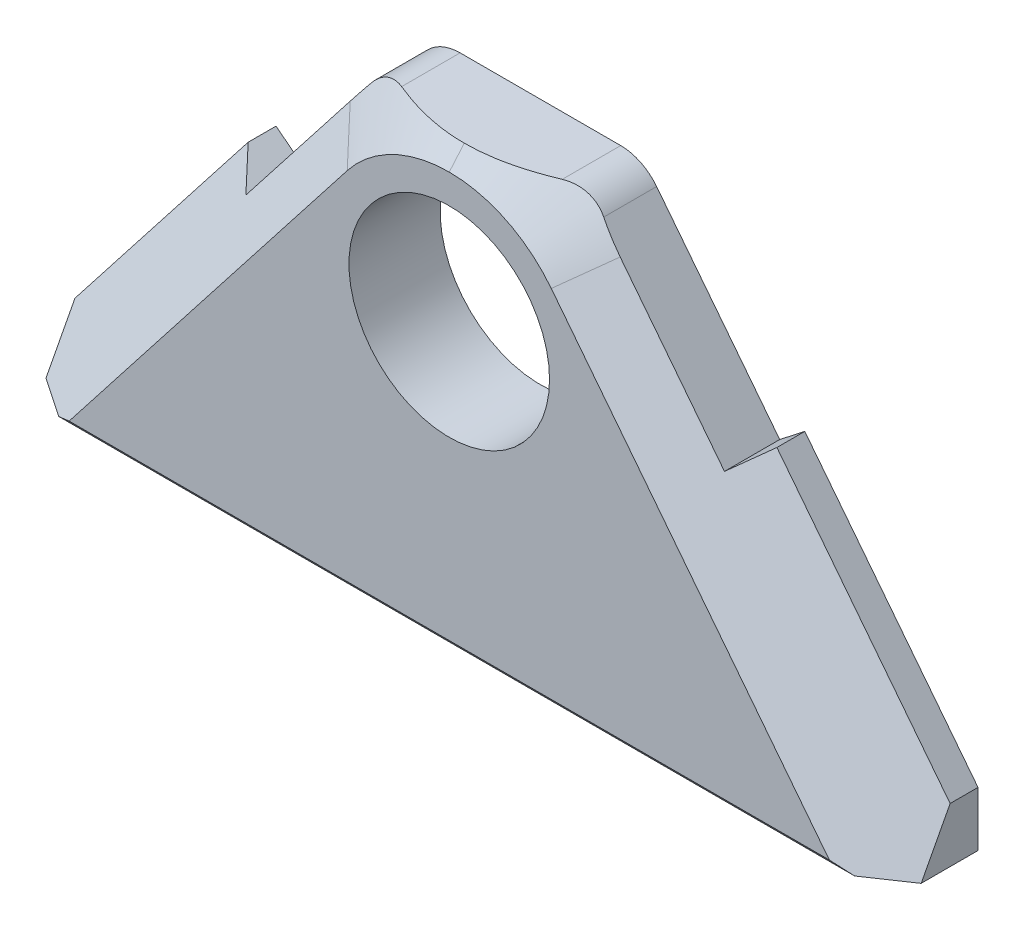
SolidWorks part; units mm, degrees
other "Markup1"
sketch "Sketch4" plane through (96, 0, 20) normal (0.9947, 0.0311, 0.0982) x (0.0936, 0.1251, -0.9877)
other "Markup3"
sketch "Sketch6" plane through (96, 0, 20) normal (0.9947, 0.0311, 0.0982) x (0.0936, 0.1251, -0.9877)
other "Markup4"
sketch "Sketch7" plane through (96, 0, 20) normal (0.9947, 0.0311, 0.0982) x (0.0936, 0.1251, -0.9877)
ref_plane "Front Plane" through (0, 0, 0) normal (0, 0, 1) x (1, 0, 0)
ref_plane "Top Plane" through (0, 0, 0) normal (0, 1, 0) x (1, 0, 0)
ref_plane "Right Plane" through (0, 0, 0) normal (1, 0, 0) x (0, 0, -1)
sketch "Sketch1" plane through (0, 0, 0) normal (0, 0, 1) x (1, 0, 0)
  line L0 (-17.6163, 0) -> (17.6163, 0)
  line L1 (25.4964, -3.8434) -> (52.5, -38.4064)
  line L2 (52.5, -38.4064) -> (58, -34.1094)
  line L3 (58, -34.1094) -> (96, -82.7471)
  line L4 (96, -82.7471) -> (96, -94.7471)
  line L5 (96, -94.7471) -> (-96, -94.7471)
  line L6 (0, -94.7471) -> (0, 0) construction
  line L7 (-96, -82.7471) -> (-96, -94.7471)
  line L8 (-58, -34.1094) -> (-96, -82.7471)
  line L9 (-52.5, -38.4064) -> (-58, -34.1094)
  line L10 (-25.4964, -3.8434) -> (-52.5, -38.4064)
  circle A0 centre (0, -32.2471) radius 22
  arc A1 (-25.4964, -3.8434) -> (-17.6163, 0) centre (-17.6163, -10) cw
  arc A2 (17.6163, 0) -> (25.4964, -3.8434) centre (17.6163, -10) cw
  point P19 (-22.4936, 0)
  point P22 (22.4936, 0)
  point P23 (22, -1.0121)
  point P24 (-22, -1.0121)
  dimension "D1" = 10
  dimension "D8" = 44
  dimension "D2" = 44
  dimension "D3" = 192
  dimension "D4" = 12
  dimension "D5" = 38
  dimension "D6" = 105
  dimension "D7" = 116
  dimension "D9" = 62.5
extrude "Boss-Extrude1" add sketch "Sketch1" along normal blind 20
sketch "Sketch2" plane through (0, 0, 20) normal (0, 0, 1) x (1, 0, 0)
  line L0 (96, -82.7471) -> (58, -34.1094) construction
  line L1 (96, -94.7471) -> (96, -82.7471) construction
  line L2 (-96, -94.7471) -> (96, -94.7471) construction
  line L3 (-96, -82.7471) -> (-96, -94.7471) construction
  line L4 (-58, -34.1094) -> (-96, -82.7471) construction
  line L5 (96, -82.7471) -> (58, -34.1094)
  line L6 (96, -94.7471) -> (96, -82.7471)
  line L7 (-96, -94.7471) -> (96, -94.7471)
  line L8 (-96, -82.7471) -> (-96, -94.7471)
  line L9 (-58, -34.1094) -> (-96, -82.7471)
  line L10 (23.8823, -13.5882) -> (87.2907, -94.7471)
  line L11 (0, 0) -> (0, -96.6519) construction
  line L12 (-23.8823, -13.5882) -> (-87.2907, -94.7471)
  line L13 (52.5, -38.4064) -> (25.4964, -3.8434) construction
  line L14 (52.5, -38.4064) -> (25.4964, -3.8434)
  line L15 (-87.2907, -94.7471) -> (87.2907, -94.7471)
  line L26 (58, -34.1094) -> (52.5, -38.4064)
  line L27 (96, -82.7471) -> (58, -34.1094)
  line L28 (96, -94.7471) -> (96, -82.7471)
  line L29 (-96, -94.7471) -> (96, -94.7471)
  line L30 (-96, -82.7471) -> (-96, -94.7471)
  line L31 (-58, -34.1094) -> (-96, -82.7471)
  line L32 (-52.5, -38.4064) -> (-58, -34.1094)
  line L33 (-25.4964, -3.8434) -> (-52.5, -38.4064)
  line L34 (17.6163, 0) -> (-17.6163, 0)
  line L35 (52.5, -38.4064) -> (25.4964, -3.8434)
  line L36 (58, -34.1094) -> (52.5, -38.4064)
  line L37 (96, -82.7471) -> (58, -34.1094)
  line L38 (96, -94.7471) -> (96, -82.7471)
  line L39 (-96, -94.7471) -> (96, -94.7471)
  line L40 (-96, -82.7471) -> (-96, -94.7471)
  line L41 (-58, -34.1094) -> (-96, -82.7471)
  line L42 (-52.5, -38.4064) -> (-58, -34.1094)
  line L43 (-25.4964, -3.8434) -> (-52.5, -38.4064)
  line L44 (17.6163, 0) -> (-17.6163, 0)
  line L45 (52.5, -38.4064) -> (25.4964, -3.8434)
  arc A0 (-23.8823, -13.5882) -> (23.8823, -13.5882) centre (0, -32.2471) cw
  arc A3 (-17.6163, 0) -> (-25.4964, -3.8434) centre (-17.6163, -10) ccw
  arc A4 (25.4964, -3.8434) -> (17.6163, 0) centre (17.6163, -10) ccw
  arc A5 (-17.6163, 0) -> (-25.4964, -3.8434) centre (-17.6163, -10) ccw
  arc A6 (25.4964, -3.8434) -> (17.6163, 0) centre (17.6163, -10) ccw
  point P9 (0, -1.94)
  dimension "D1" = 52
  dimension "D2" = 0
  dimension "D3" = 1.94
sketch "Sketch3" plane through (0, 0, 0) normal (1, 0, 0) x (0, 0, -1)
  line L0 (-20, -3.8434) -> (-20, 31.0595)
  line L1 (10, 31.0595) -> (-20, 31.0595)
  line L3 (10, 31.0595) -> (-20, -3.8434)
  dimension "D1" = 40.68
  dimension "D2" = 30
sweep "Cut-Sweep3" cut profiles "Sketch3" path "Sketch2"
